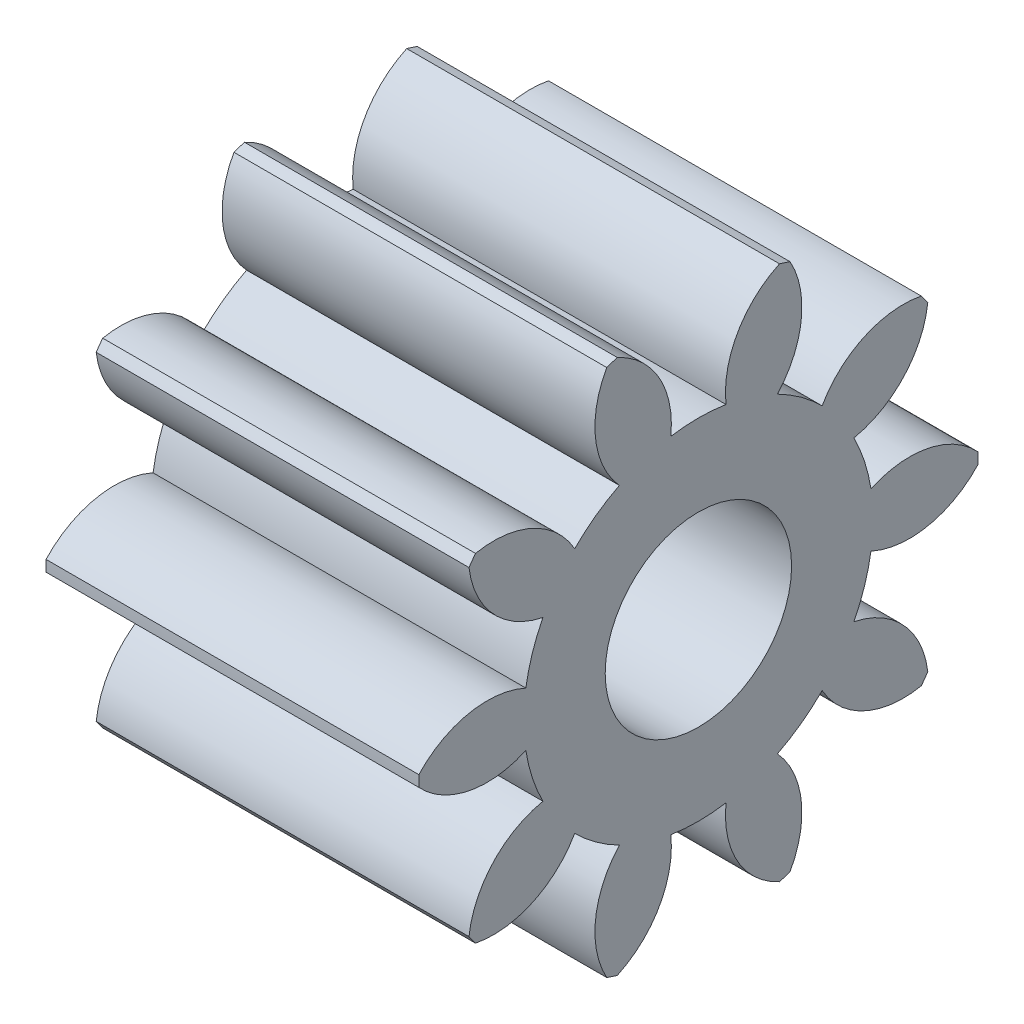
SolidWorks part; units mm, degrees
ref_plane "Plane1" through (0, 0, 0) normal (0, 0, 1) x (1, 0, 0)
ref_plane "Plane2" through (0, 0, 0) normal (0, 1, 0) x (1, 0, 0)
ref_plane "Plane3" through (0, 0, 0) normal (1, 0, 0) x (0, 0, -1)
other "Configuration Table"
sketch "HoldingSke" plane through (0, 0, 0) normal (0, 1, 0) x (1, 0, 0)
  line L0 (0, 0) -> (1.9696, -0.3473)
  line L1 (-15, 0) -> (100, 0) construction
  line L2 (0, 0) -> (-2.1039, 2.3779)
  line L3 (0, 0) -> (-11.863, 4.5341)
  line L4 (0, 0) -> (8.5048, 1.4996)
  line L5 (0, 0) -> (-46.8476, -17.4728)
  line L6 (0, 0) -> (-3.3159, -2.2372)
  line L7 (-2.1039, 2.3779) -> (8.6586, 51.2059)
  line L8 (-76.2, 54.61) -> (-75.9, 54.61)
  line L9 (-71.009, 38.7566) -> (-53.1078, 45.2721)
  line L10 (-76.2, 71.12) -> (104.1128, 71.12)
  line L11 (0, 0) -> (-4, 0)
  line L12 (-76.2, 101.6) -> (-76.181, 101.6)
  line L13 (24.9733, 27.94) -> (52.9518, 28.4284)
  line L14 (24.9733, 27.94) -> (24.9743, 27.94)
  line L15 (24.9733, 27.94) -> (100.4006, 29.5858)
  line L16 (-63.627, -0.5) -> (-12.827, -0.5)
  circle A0 centre (0, 0) radius 1
  circle A1 centre (0, 0) radius 1.874
  circle A2 centre (0, 0) radius 37.5
  circle A3 centre (0, 0) radius 1
  dimension "MHD" = 3.748
  dimension "Hub_dia" = 75
  dimension "Bore" = 2
  dimension "MBD" = 2
  dimension "Num_teeth" = 10
  dimension "Pitch" = 2
  dimension "Overall_len" = 50
  dimension "Show_teeth" = 10
  dimension "Thickness" = 4
  dimension "OAL" = 50.0001
  dimension "T_dim" = 0.3
  dimension "Ap" = 20
  dimension "H" = 19.05
  dimension "Pitch_radius" = 180.3128
  dimension "Width" = 4
  dimension "Backlash" = 0.019
  dimension "Addendum_fac" = 1
  dimension "Dedendum_fac" = 1.25
  dimension "Clearance_fac" = 0.25
  dimension "Dedendum_add" = 0.001
  dimension "Module" = 0.5
sketch "BasProSke" plane through (0, 0, 0) normal (0, 1, 0) x (1, 0, 0)
  line L0 (-10, 0) -> (60, 0) construction
  line L1 (0, 0) -> (0, 3)
  line L2 (0, 0) -> (4, 0)
  line L3 (4, 0) -> (4, 3)
  line L4 (4, 3) -> (0, 3)
  dimension "Thickness" = 4
  dimension "Diameter" = 6
revolve "Base-Revolve" add sketch "BasProSke" angle 360 about L0
sketch "TooCutSke" plane through (0, 0, 0) normal (1, 0, 0) x (0, 0, -1)
  line L1 (0, 0) -> (0, 107) construction
  line L2 (0, 0) -> (-0.4243, 2.4637) construction
  line L3 (0, 0) -> (-1.5292, 4.7063) construction
  line L4 (-0.4243, 2.4637) -> (-0.7646, 2.3532) construction
  arc A0 (0.2964, 1.8504) -> (-0.2964, 1.8504) centre (0, 0) ccw
  arc A1 (0.9059, 2.8866) -> (-0.9059, 2.8866) centre (0, 0) ccw
  circle A2 centre (0, 0) radius 2.5 construction
  circle A3 centre (0, 0) radius 2.3492 construction
  arc A4 (-0.2964, 1.8504) -> (-0.9059, 2.8866) centre (-1.2901, 1.9633) ccw
  arc A5 (0.9059, 2.8866) -> (0.2964, 1.8504) centre (1.2901, 1.9633) ccw
  dimension "Root_dia" = 3.748
  dimension "Overcut_dia" = 6.0508
  dimension "Pitch_dia" = 5
  dimension "Base_dia" = 4.6985
  dimension "Flank_rad" = 1
  dimension "Half_ang" = 18
  dimension "Half_CT" = 0.3578
extrude "ToothCut" cut sketch "TooCutSke" along normal through all
fillet "Breaks" [suppressed] radius 0.01
fillet "RootFillets" [suppressed] radius 0.126
pattern_circular "TeethCuts" count 10 every 36 about axis through (-10, 0, 0) along (1, 0, 0) of "ToothCut", "RootFillets", "Breaks"
sketch "HubNeaOneSke" plane through (0, 0, 0) normal (-1, 0, 0) x (0, 0, 1)
  circle A0 centre (0, 0) radius 1.874
  dimension "Diameter" = 3.748
extrude "HubNearOne" [suppressed] add sketch "HubNeaOneSke" along normal blind 46.0001
sketch "HubNeaBotSke" plane through (0, 0, 0) normal (-1, 0, 0) x (0, 0, 1)
  circle A0 centre (0, 0) radius 1.874
  dimension "Diameter" = 3.748
extrude "HubNearBoth" [suppressed] add sketch "HubNeaBotSke" along normal blind 23
ref_plane "FarPln" through (4, 0, 0) normal (1, 0, 0) x (0, 0, -1)
sketch "HubFarSke" plane through (4, 0, 0) normal (1, 0, 0) x (0, 0, -1)
  circle A0 centre (0, 0) radius 1.874
  dimension "Diameter" = 3.748
extrude "HubFar" [suppressed] add sketch "HubFarSke" along normal blind 23
sketch "BorSke" plane through (0, 0, 0) normal (1, 0, 0) x (0, 0, -1)
  circle A0 centre (0, 0) radius 1
  dimension "Diameter" = 2
extrude "Bore" cut sketch "BorSke" along normal mid plane 100.0001
sketch "KeySke" plane through (0, 0, 0) normal (1, 0, 0) x (0, 0, -1)
  line L0 (-0.4, 0) -> (-0.4, 1.3)
  line L1 (-0.4, 1.3) -> (0.4, 1.3)
  line L2 (0.4, 1.3) -> (0.4, 0)
  line L3 (0, 0) -> (0, 34) construction
  line L4 (-0.4, 0) -> (0.4, 0)
  dimension "Offset" = 1.3
  dimension "Width" = 0.8
extrude "Keyway" [suppressed] cut sketch "KeySke" along normal mid plane 100.0001
pattern_circular "Keyway2" [suppressed] count 2 every 90 about axis through (-10, 0, 0) along (1, 0, 0)
ref_plane "Plane4" through (2, 0, 0) normal (1, 0, 0) x (0, 0, -1)
equation "' \"Module@HoldingSke\" = 6.35"
equation "' \"Num_teeth@HoldingSke\" = 12"
equation "' \"Ap@HoldingSke\" =  20"
equation "' \"Ap@HoldingSke\" = 20"
equation "' \"Width@HoldingSke\" = 0.5 * 25.4"
equation "' \"Hub_dia@HoldingSke\"= 1 * 25.4"
equation "' \"Hub_dia@HoldingSke\" = 1 * 25.4"
equation "' \"Overall_len@HoldingSke\" = 1.0 * 25.4"
equation "' \"Bore@HoldingSke\" = 0.75 * 25.4"
equation "' \"T_dim@HoldingSke\" = 0.1 * 25.4"
equation "' \"Width@KeySke\" = 0.25 * 25.4"
equation "' \"Show_teeth@HoldingSke\" = 13"
equation "' \"Backlash@HoldingSke\" = 0.009 * 25.4"
equation "' \"Addendum_fac@HoldingSke\" = 1.0"
equation "' \"Dedendum_fac@HoldingSke\" = 1.25"
equation "' \"Dedendum_add@HoldingSke\" = 0.00005 * 25.4"
equation "' \"Clearance_fac@HoldingSke\" = 0.25"
equation "\"Pitch@HoldingSke\" = 1 / \"Module@HoldingSke\""
equation "\"Overcut_dia@TooCutSke\" = (\"Num_teeth@HoldingSke\" + 2 * \"Addendum_fac@HoldingSke\") / \"Pitch@HoldingSke\" + 0.002 * 25.4"
equation "\"Pitch_dia@TooCutSke\" = \"Num_teeth@HoldingSke\" / \"Pitch@HoldingSke\""
equation "\"Base_dia@TooCutSke\" = \"Num_teeth@HoldingSke\" / \"Pitch@HoldingSke\" * cos((\"Ap@HoldingSke\"  * 3.14159265 / 180))"
equation "\"Root_dia@TooCutSke\" = (\"Num_teeth@HoldingSke\" + 2) / \"Pitch@HoldingSke\" - 2 * (\"Addendum_fac@HoldingSke\" + \"Dedendum_fac@HoldingSke\") / \"Pitch@HoldingSke\" - \"Dedendum_add@HoldingSke\" * 2"
equation "\"Half_ang@TooCutSke\" = 180 / \"Num_teeth@HoldingSke\""
equation "\"Half_CT@TooCutSke\" = \"Num_teeth@HoldingSke\" / \"Pitch@HoldingSke\" * sin((3.14159265 / 2 / \"Num_teeth@HoldingSke\")) / 2 - 7 * \"Backlash@HoldingSke\" / 4"
equation "\"Flank_rad@TooCutSke\" = \"Num_teeth@HoldingSke\" / \"Pitch@HoldingSke\" / 5"
equation "\"Radius@RootFillets\" = \"Clearance_fac@HoldingSke\" / \"Pitch@HoldingSke\" + \"Dedendum_add@HoldingSke\""
equation "\"Break_rad@Breaks\" = 0.02 / \"Pitch@HoldingSke\""
equation "\"Thickness@HoldingSke\" = \"Width@HoldingSke\""
equation "\"OAL@HoldingSke\" = \"Thickness@HoldingSke\""
equation "\"MHD@HoldingSke\" = (\"Num_teeth@HoldingSke\" + 2) / \"Pitch@HoldingSke\" - 2 * (\"Addendum_fac@HoldingSke\" + \"Dedendum_fac@HoldingSke\")  / \"Pitch@HoldingSke\" - \"Dedendum_add@HoldingSke\" * 2"
equation "\"MBD@HoldingSke\" = (\"Num_teeth@HoldingSke\" + 2) / \"Pitch@HoldingSke\" - 2 * (\"Addendum_fac@HoldingSke\" + \"Dedendum_fac@HoldingSke\")  / \"Pitch@HoldingSke\" - \"Dedendum_add@HoldingSke\" * 2 - 0.002 * 25.4"
equation "\"MHD@HoldingSke\" = ((sgn( \"MHD@HoldingSke\" - \"Hub_dia@HoldingSke\" )-1)*( \"MHD@HoldingSke\" - \"Hub_dia@HoldingSke\" ))/-2+ \"Hub_dia@HoldingSke\""
equation "\"MBD@HoldingSke\" = ((sgn( \"MBD@HoldingSke\" - \"Bore@HoldingSke\" )-1)*( \"MBD@HoldingSke\" - \"Bore@HoldingSke\" ))/-2+ \"Bore@HoldingSke\""
equation "\"OAL@HoldingSke\" = ((sgn( \"OAL@HoldingSke\" - \"Overall_len@HoldingSke\" )+1)*( \"OAL@HoldingSke\" - \"Overall_len@HoldingSke\" ))/2 + \"Overall_len@HoldingSke\" + 0.000002 * 25.4"
equation "\"Num_teeth@TeethCuts\" = int( \"Show_teeth@HoldingSke\" ) + 1"
equation "\"Num_teeth@TeethCuts\" = ((sgn( \"Num_teeth@TeethCuts\" - \"Num_teeth@HoldingSke\" )-1)*( \"Num_teeth@TeethCuts\" - \"Num_teeth@HoldingSke\" ))/-2+ \"Num_teeth@HoldingSke\""
equation "\"Num_teeth@TeethCuts\" = ((sgn( \"Num_teeth@TeethCuts\" - 2.0)+1)*( \"Num_teeth@TeethCuts\" - 2.0))/2 +2.0"
equation "\"Angle@TeethCuts\" = 360.0 / \"Num_teeth@HoldingSke\""
equation "\"Diameter@BasProSke\" = (\"Num_teeth@HoldingSke\" + 2 * \"Addendum_fac@HoldingSke\") / \"Pitch@HoldingSke\""
equation "\"Thickness@BasProSke\"  = \"Thickness@HoldingSke\""
equation "' \"Fillet_rad@BasProSke\" =  \"Thickness@HoldingSke\" * 0.05"
equation "' \"Fillet_rad@BasProSke\" = \"Thickness@HoldingSke\" * 0.05"
equation "\"MHD@HoldingSke\" = ((sgn( \"MHD@HoldingSke\" - \"Root_dia@TooCutSke\" )-1)*( \"MHD@HoldingSke\" - \"Root_dia@TooCutSke\" ))/-2+ \"Root_dia@TooCutSke\""
equation "\"Diameter@HubNeaOneSke\" = \"MHD@HoldingSke\""
equation "\"Length@HubNearOne\" = \"OAL@HoldingSke\" - \"Thickness@BasProSke\""
equation "\"Diameter@HubNeaBotSke\" = \"MHD@HoldingSke\""
equation "\"Length@HubNearBoth\" = ( \"OAL@HoldingSke\" - \"Thickness@BasProSke\" ) / 2.0"
equation "\"Thickness@FarPln\" = \"Thickness@BasProSke\""
equation "\"Diameter@HubFarSke\" = \"MHD@HoldingSke\""
equation "\"Length@HubFar\" = ( \"OAL@HoldingSke\" - \"Thickness@BasProSke\" ) / 2.0"
equation "\"Diameter@BorSke\" = \"MBD@HoldingSke\""
equation "\"D1@Bore\" = \"OAL@HoldingSke\" * 2.0"
equation "\"D1@Keyway\" = \"OAL@HoldingSke\" * 2.0"
equation "\"Offset@KeySke\" = \"T_dim@HoldingSke\" + \"MBD@HoldingSke\" / 2.0"
